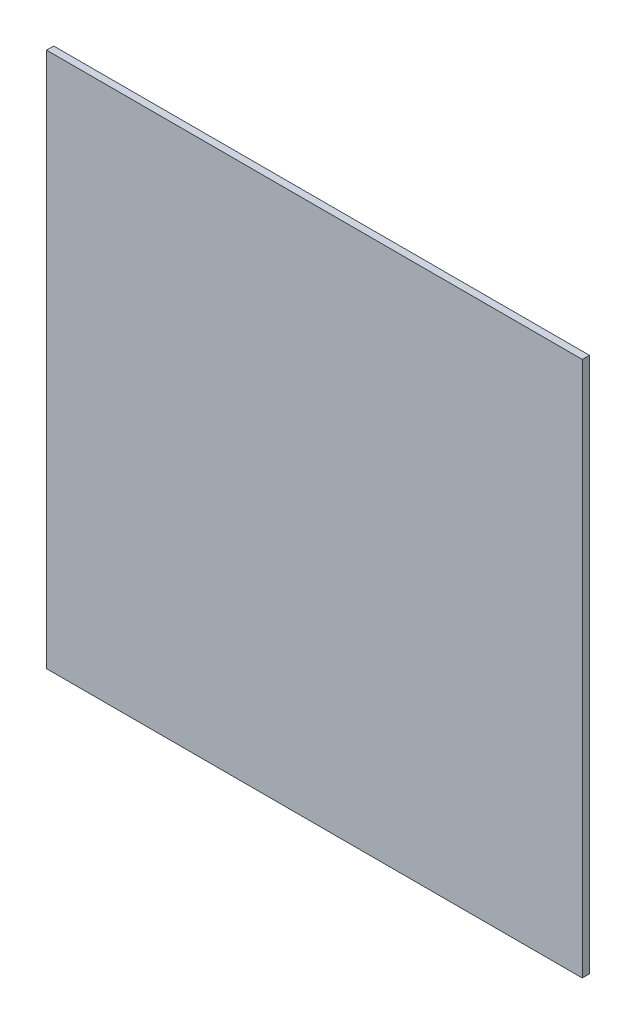
SolidWorks part; units mm, degrees
material "Acrylic (Medium-high impact)"
ref_plane "Front Plane" through (0, 0, 0) normal (0, 0, 1) x (1, 0, 0)
ref_plane "Top Plane" through (0, 0, 0) normal (0, 1, 0) x (1, 0, 0)
ref_plane "Right Plane" through (0, 0, 0) normal (1, 0, 0) x (0, 0, -1)
sketch "Sketch1" plane through (0, 0, 0) normal (0, 0, 1) x (1, 0, 0)
  line L1 (0, 0) -> (224, 0)
  line L2 (0, 0) -> (0, 224)
  line L3 (0, 224) -> (224, 224)
  line L4 (224, 0) -> (224, 224)
  dimension "D1" = 224
  dimension "D2" = 224
extrude "Boss-Extrude1" add sketch "Sketch1" along normal blind 3
